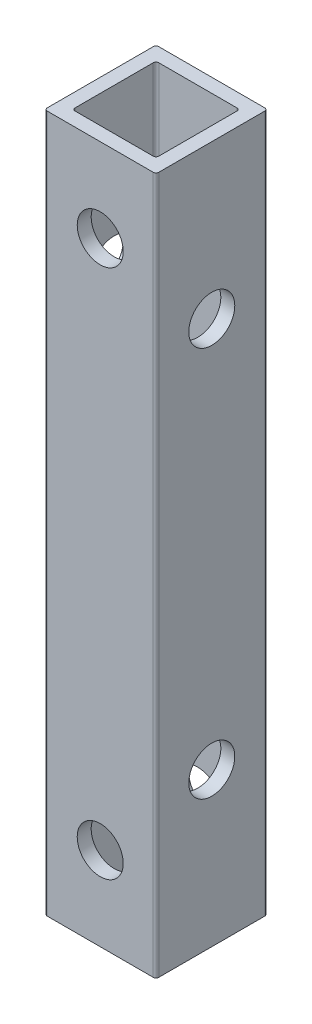
SolidWorks part; units mm, degrees
ref_plane "前视基准面" through (0, 0, 0) normal (0, 0, 1) x (1, 0, 0)
ref_plane "上视基准面" through (0, 0, 0) normal (0, 1, 0) x (1, 0, 0)
ref_plane "右视基准面" through (0, 0, 0) normal (1, 0, 0) x (0, 0, -1)
sketch "草图1" plane through (0, 0, 0) normal (0, 1, 0) x (1, 0, 0)
  line L1 (-4, 4) -> (4, 4)
  line L2 (-4, 4) -> (-4, -4)
  line L3 (-4, -4) -> (4, -4)
  line L4 (4, 4) -> (4, -4)
  line L5 (0, -4) -> (0, 4) construction
  line L6 (-4, 0) -> (4, 0) construction
  line L7 (-3, 3) -> (3, 3)
  line L8 (-3, 3) -> (-3, -3)
  line L9 (-3, -3) -> (3, -3)
  line L10 (3, 3) -> (3, -3)
  line L11 (0, -3) -> (0, 3) construction
  line L12 (-3, 0) -> (3, 0) construction
  point P0 (0, 0)
  point P4 (0, 0)
  dimension "D1" = 8
  dimension "D2" = 8
  dimension "D3" = 1
  dimension "D4" = 1
extrude "凸台-拉伸1" add sketch "草图1" along normal blind 50
fillet "圆角1" radius 0.2 4 edges at (3, 25, 3) (-3, 25, 3) (3, 25, -3) (-3, 25, -3)
fillet "圆角2" radius 0.2 4 edges at (-4, 25, 4) (4, 25, 4) (-4, 25, -4) (4, 25, -4)
sketch "草图3" plane through (4, 0, 0) normal (1, 0, 0) x (0, 0, -1)
  line L0 (0, 50) -> (0, 0) construction
  line L1 (-3.8, 50) -> (3.8, 50) construction
  line L2 (-4, 25) -> (4, 25) construction
  line L5 (-4, 0) -> (-4, 50) construction
  line L6 (4, 50) -> (4, 0) construction
  circle A0 centre (0, 39) radius 1.65
  circle A1 centre (0, 11) radius 1.65
  dimension "D1" = 3.3
  dimension "D2" = 28
extrude "切除-拉伸1" cut sketch "草图3" against normal blind 50
sketch "草图4" plane through (0, 0, -4) normal (0, 0, -1) x (-1, 0, 0)
  line L0 (0, 50) -> (0, 0) construction
  line L1 (-3.8, 50) -> (3.8, 50) construction
  line L2 (-4, 25) -> (4, 25) construction
  line L3 (-4, 0) -> (-4, 50) construction
  line L4 (4, 50) -> (4, 0) construction
  circle A0 centre (0, 44) radius 1.65
  circle A1 centre (0, 6) radius 1.65
  dimension "D1" = 38
  dimension "D2" = 3.3
extrude "切除-拉伸2" cut sketch "草图4" against normal blind 50
